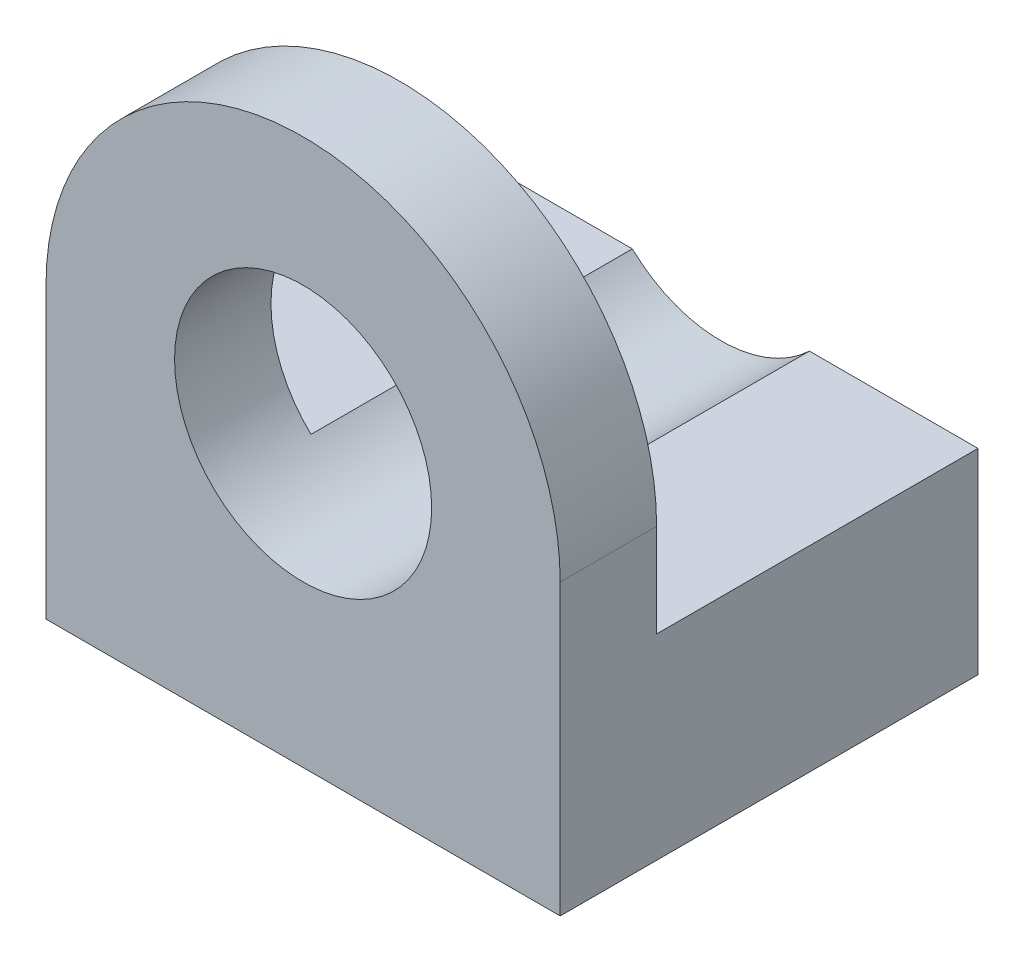
SolidWorks part; units mm, degrees
ref_plane "Front Plane" through (0, 0, 0) normal (0, 0, 1) x (1, 0, 0)
ref_plane "Top Plane" through (0, 0, 0) normal (0, 1, 0) x (1, 0, 0)
ref_plane "Right Plane" through (0, 0, 0) normal (1, 0, 0) x (0, 0, -1)
sketch "Sketch1" plane through (0, 0, 0) normal (0, 0, 1) x (1, 0, 0)
  line L0 (-40, 0) -> (-40, -45)
  line L1 (-40, -45) -> (40, -45)
  line L2 (40, -45) -> (40, 0)
  circle A0 centre (0, 0) radius 40
  circle A1 centre (0, 0) radius 20
  dimension "D1" = 80
  dimension "D2" = 40
  dimension "D3" = 45
extrude "Boss-Extrude1" add sketch "Sketch1" along normal blind 15 contours A0 A1 | A0 L0 L1 L2
sketch "Sketch3" plane through (0, 0, 0) normal (0, 0, -1) x (-1, 0, 0)
  line L1 (13.775, -14.5) -> (40, -14.5)
  line L2 (40, 0) -> (40, -45) construction
  line L3 (40, -14.5) -> (40, -45)
  line L4 (40, -45) -> (-40, -45)
  line L5 (-40, -45) -> (-40, -14.5)
  line L6 (-40, -45) -> (-40, 0) construction
  line L7 (-40, -14.5) -> (-13.775, -14.5)
  arc A0 (-13.775, -14.5) -> (13.775, -14.5) centre (0, 0) ccw
  circle A1 centre (0, 0) radius 20 construction
extrude "Boss-Extrude2" add sketch "Sketch3" along normal blind 50
